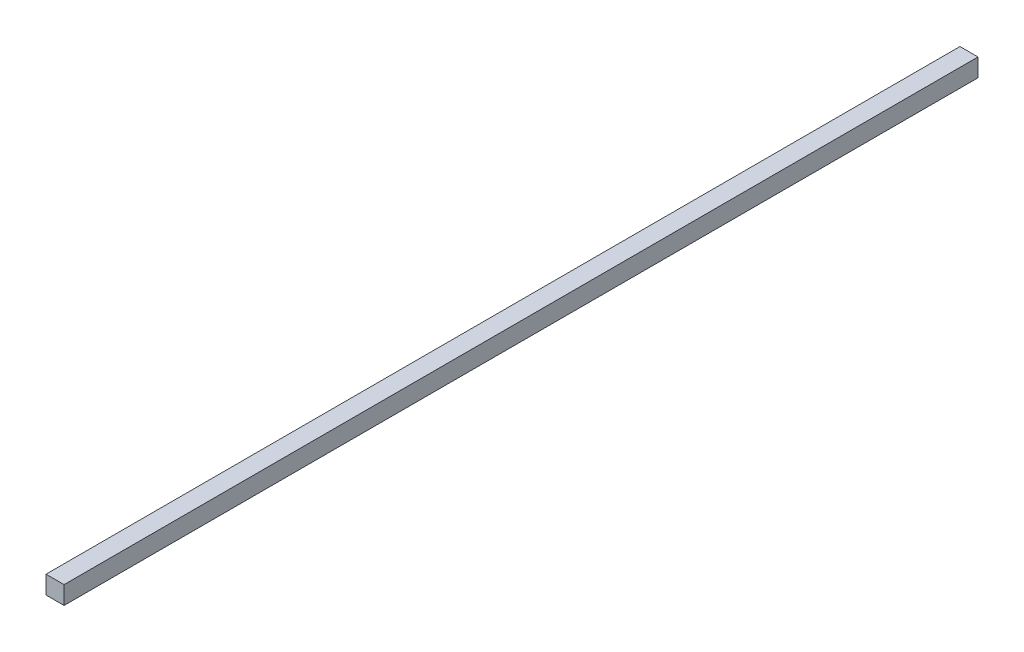
SolidWorks part; units mm, degrees
material "Balsa"
ref_plane "Front Plane" through (0, 0, 0) normal (0, 0, 1) x (1, 0, 0)
ref_plane "Top Plane" through (0, 0, 0) normal (0, 1, 0) x (1, 0, 0)
ref_plane "Right Plane" through (0, 0, 0) normal (1, 0, 0) x (0, 0, -1)
sketch "Sketch1" plane through (0, 0, 0) normal (0, 0, 1) x (1, 0, 0)
  line L1 (-3.175, 3.175) -> (3.175, 3.175)
  line L2 (-3.175, 3.175) -> (-3.175, -3.175)
  line L3 (-3.175, -3.175) -> (3.175, -3.175)
  line L4 (3.175, 3.175) -> (3.175, -3.175)
  line L5 (-3.175, 3.175) -> (3.175, -3.175) construction
  line L6 (-3.175, -3.175) -> (3.175, 3.175) construction
  point P0 (0, 0)
  dimension "D1" = 6.35
  dimension "D2" = 6.35
extrude "Boss-Extrude1" add sketch "Sketch1" along normal blind 321.31
